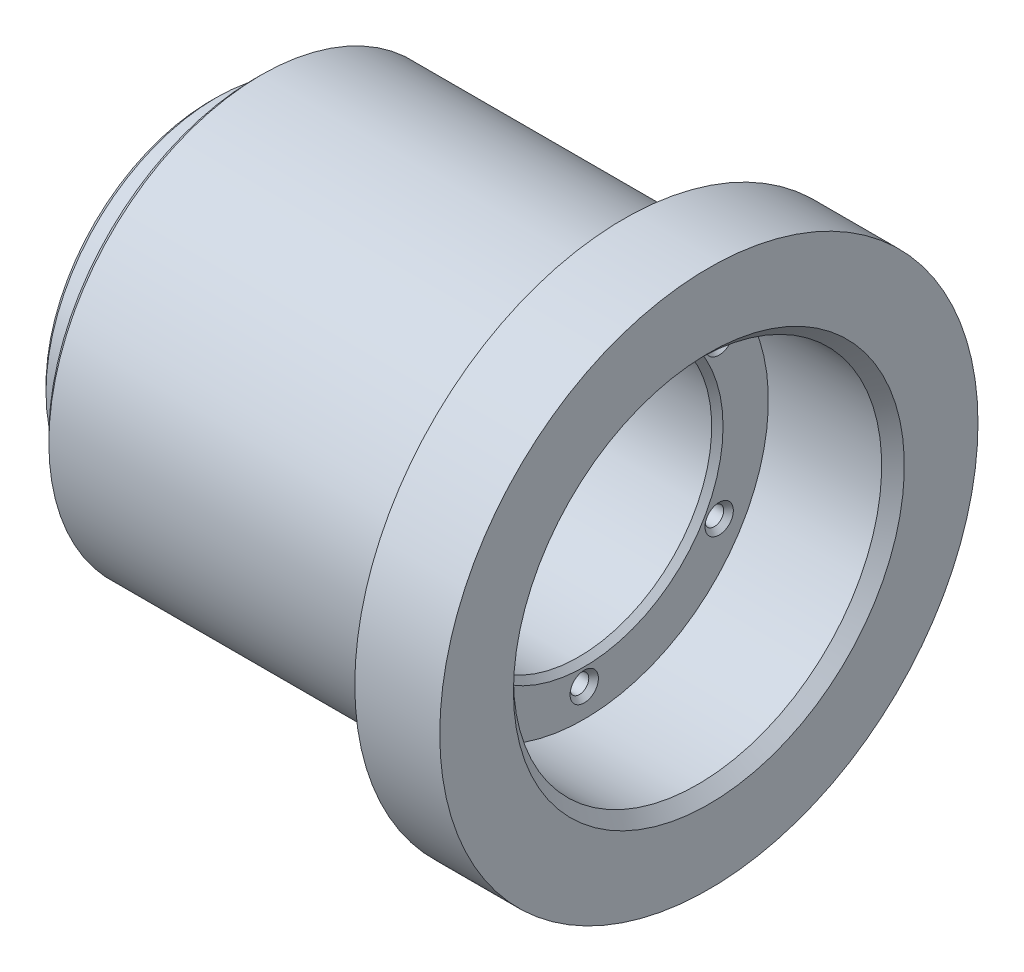
SolidWorks part; units mm, degrees
material "1060-H16"
ref_plane "Спереди" through (0, 0, 0) normal (0, 0, 1) x (1, 0, 0)
ref_plane "Сверху" through (0, 0, 0) normal (0, 1, 0) x (1, 0, 0)
ref_plane "Справа" through (0, 0, 0) normal (1, 0, 0) x (0, 0, -1)
sketch "Эскиз1" plane through (0, 0, 0) normal (0, 0, 1) x (1, 0, 0)
  line L0 (0, 0) -> (91, 0) construction
  line L3 (-48, 15) -> (-48, 30)
  line L4 (-48, 30) -> (-40, 30)
  line L5 (-40, 30) -> (-40, 47.5)
  line L6 (-40, 47.5) -> (40, 47.5)
  line L7 (40, 47.5) -> (40, 32.5)
  line L8 (40, 32.5) -> (18, 32.5)
  line L9 (18, 32.5) -> (18, 23.5)
  line L10 (18, 23.5) -> (-18, 23.5)
  line L11 (-18, 23.5) -> (-18, 21)
  line L12 (-21, 15) -> (-48, 15)
  line L14 (0, 47.5) -> (0, -49952.5) construction
  line L15 (-18, 21) -> (-21, 21)
  line L16 (-21, 21) -> (-21, 15)
  point P9 (-40, 47.5)
  point P10 (40, 47.5)
  point P11 (40, 32.5)
  point P13 (18, 23.5)
  point P15 (-18, 15)
  point P17 (0, 47.5)
  dimension "D2" = 30
  dimension "D5" = 60
  dimension "D6" = 8
  dimension "D7" = 30
  dimension "D8" = 65
  dimension "D9" = 80
  dimension "D10" = 95
  dimension "D11" = 47
  dimension "D12" = 42
  dimension "D13" = 3
revolve "Повернуть1" add sketch "Эскиз1" angle 360 about L0
hole_wizard "Отверстие обработанное метчиком M61" positions "Эскиз6" profile "Эскиз5" tap size "M6" standard "DIN"
sketch "Эскиз6" plane through (-48, 0, 0) normal (-1, 0, 0) x (0, 0, 1)
  line L0 (0, 0) -> (0, 24) construction
  circle A2 centre (0, 0) radius 24
  point P0 (0, 24)
  point P22 (20.7846, 12)
  point P23 (20.7846, -12)
  point P24 (0, -24)
  point P25 (-20.7846, -12)
  point P26 (-20.7846, 12)
  dimension "D1" = 48
  dimension "D2" = 6
sketch "Эскиз5" plane through (-48, 24, 0) normal (0, 1, 0) x (0, 0, 1)
  line L0 (0, 0) -> (0, 19.5022)
  line L1 (0, 19.5022) -> (2.5, 18)
  line L2 (2.5, 18) -> (2.5, 0)
  line L5 (2.5, 0) -> (0, 0)
  line L10 (0, 19.5022) -> (-2.5, 18) construction
  line L11 (0, -6.35) -> (0, 107.95) construction
  dimension "Диаметр сверла" = 5
  dimension "Глубина сверла" = 18
  dimension "Угол заточки сверла" = 118
cosmetic thread "Отверстие резьбы1" parameters "D1"=15, "D2"=6
cosmetic thread "Отверстие резьбы2" parameters "D1"=15, "D2"=6
cosmetic thread "Отверстие резьбы3" parameters "D1"=15, "D2"=6
cosmetic thread "Отверстие резьбы4" parameters "D1"=15, "D2"=6
cosmetic thread "Отверстие резьбы5" parameters "D1"=15, "D2"=6
cosmetic thread "Отверстие резьбы6" parameters "D1"=15, "D2"=6
hole_wizard "Отверстие обработанное метчиком M44" positions "Эскиз9" profile "Эскиз10" tap size "M4" standard "DIN"
sketch "Эскиз9" plane through (18, 0, 0) normal (1, 0, 0) x (0, 0, -1)
  circle A1 centre (0, 0) radius 27.5 construction
  point P0 (0, 27.5)
  dimension "D1" = 55
sketch "Эскиз10" plane through (18, 27.5, 0) normal (0, 1, 0) x (0, 0, -1)
  line L0 (0, 0) -> (0, 16.9914)
  line L1 (0, 16.9914) -> (1.65, 16)
  line L2 (1.65, 16) -> (1.65, 0.85)
  line L3 (1.65, 0.85) -> (2.5, 0)
  line L5 (2.5, 0) -> (0, 0)
  line L6 (-1.65, 0.85) -> (-2.5, 0) construction
  line L10 (0, 16.9914) -> (-1.65, 16) construction
  line L11 (0, -6.35) -> (0, 107.95) construction
  dimension "Диаметр сверла" = 3.3
  dimension "Глубина сверла" = 16
  dimension "Диаметр передней зенковки" = 5
  dimension "Угол передней зенковки" = 90
  dimension "Угол заточки сверла" = 118
cosmetic thread "Отверстие резьбы18" parameters "D1"=12, "D2"=4
chamfer "Фаска2" distance 1 angle 45 6 edges at (-48, 24, 2.5) (-48, 12, 23.2846) (-48, -12, 23.2846) (-48, -24, 2.5) (-48, -12, -18.2846) (-48, 12, -18.2846)
sketch "Эскиз12" plane through (-48, 0, 0) normal (-1, 0, 0) x (0, 0, 1)
  circle A0 centre (0, 0) radius 15 construction
  circle A1 centre (0, 0) radius 15
  circle A2 centre (0, 0) radius 18
  dimension "D1" = 36
extrude "Вырез-Вытянуть1" cut sketch "Эскиз12" against normal blind 4
sketch "Эскиз11" plane through (0, 0, 0) normal (0, 0, 1) x (1, 0, 0)
  line L0 (-40, 37.5) -> (25, 37.5)
  line L1 (-40, 47.5) -> (-40, -47.5) construction
  line L2 (25, 37.5) -> (25, 47.5)
  line L3 (40, 47.5) -> (-40, 47.5) construction
  line L4 (25, 47.5) -> (-40, 47.5)
  line L5 (-40, 47.5) -> (-40, 37.5)
  line L7 (0, 0) -> (-50000, 0) construction
  dimension "D1" = 75
  dimension "D2" = 65
revolve "Вырез-Повернуть1" cut sketch "Эскиз11" angle 360 about L7
pattern_circular "Круговой массив1" count 6 over 360 about axis through (0, 0, 0) along (1, 0, 0) of "Отверстие обработанное метчиком M44"
cosmetic thread "Отверстие резьбы19" parameters "D1"=12, "D2"=4
cosmetic thread "Отверстие резьбы20" parameters "D1"=12, "D2"=4
cosmetic thread "Отверстие резьбы21" parameters "D1"=12, "D2"=4
cosmetic thread "Отверстие резьбы22" parameters "D1"=12, "D2"=4
cosmetic thread "Отверстие резьбы23" parameters "D1"=12, "D2"=4
chamfer "Фаска3" distance 5 angle 45 1 edges at (25, 0, -37.5)
chamfer "Фаска4" distance 2 angle 45 1 edges at (40, 0, 32.5)
chamfer "Фаска5" distance 1 angle 45 5 edges at (-40, 0, -37.5) (-48, 0, 30) (18, 0, 23.5) (-44, 0, 15) (-48, 0, 18)
